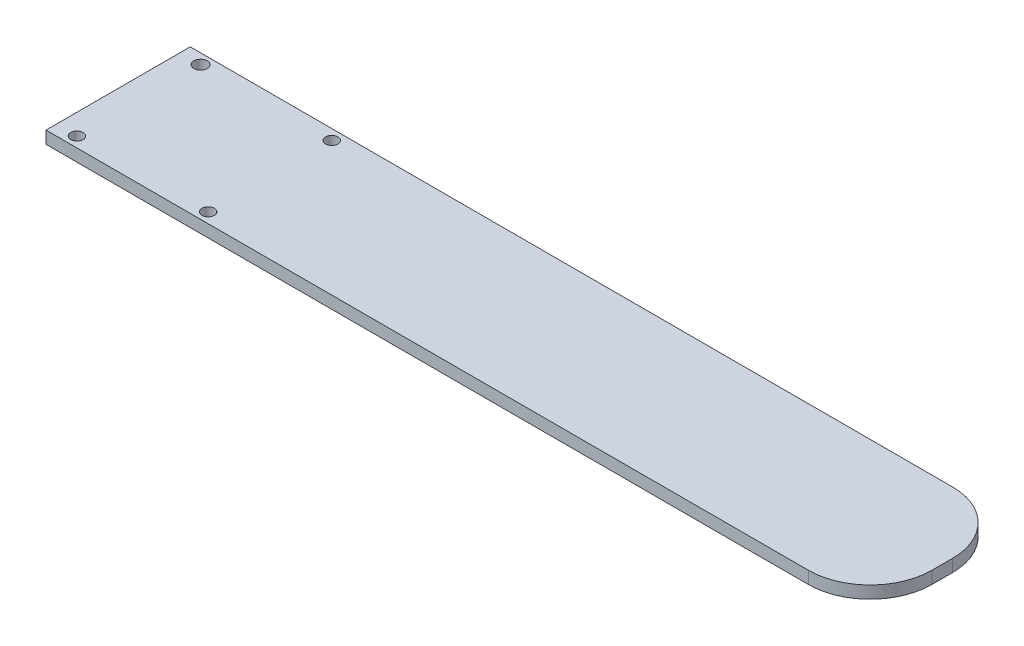
SolidWorks part; units mm, degrees
ref_plane "Front Plane" through (0, 0, 0) normal (0, 0, 1) x (1, 0, 0)
ref_plane "Top Plane" through (0, 0, 0) normal (0, 1, 0) x (1, 0, 0)
ref_plane "Right Plane" through (0, 0, 0) normal (1, 0, 0) x (0, 0, -1)
sketch "Sketch1" plane through (0, 0, 0) normal (0, 1, 0) x (1, 0, 0)
  line L1 (100, -17.5) -> (-100, -17.5)
  line L2 (100, -17.5) -> (100, 17.5)
  line L3 (100, 17.5) -> (-100, 17.5)
  line L4 (-100, -17.5) -> (-100, 17.5)
  line L5 (100, -17.5) -> (-100, 17.5) construction
  line L6 (100, 17.5) -> (-100, -17.5) construction
  point P0 (0, 0)
  dimension "D1" = 200
  dimension "D2" = 35
extrude "Boss-Extrude1" add sketch "Sketch1" along normal blind 3
fillet "Fillet1" radius 15 2 edges at (100, 1.5, -17.5) (100, 1.5, 17.5)
sketch "Sketch2" plane through (0, 3, 0) normal (0, 1, 0) x (1, 0, 0)
  line L1 (-100, 17.5) -> (-40, 17.5)
  line L2 (-100, 17.5) -> (-100, -17.5)
  line L3 (-100, -17.5) -> (-40, -17.5)
  line L4 (100, -2.5) -> (100, 2.5)
  line L5 (85, 17.5) -> (-100, 17.5)
  line L6 (-100, 17.5) -> (-100, -17.5)
  line L7 (-100, -17.5) -> (85, -17.5)
  line L8 (100, -2.5) -> (100, 2.5)
  line L9 (85, 17.5) -> (-100, 17.5)
  line L10 (-100, 17.5) -> (-100, -17.5)
  line L11 (-100, -17.5) -> (85, -17.5)
  line L12 (-40, 17.5) -> (-40, -17.5)
  line L13 (-63.144, -15) -> (-95, -15)
  line L14 (-63.144, -15) -> (-63.144, 15)
  line L15 (-63.144, 15) -> (-95, 15)
  line L16 (-95, -15) -> (-95, 15)
  line L17 (-63.144, -15) -> (-95, 15) construction
  line L18 (-63.144, 15) -> (-95, -15) construction
  circle A0 centre (-95, 15) radius 1.623
  circle A1 centre (-63.144, 15) radius 1.5
  arc A2 (100, 2.5) -> (85, 17.5) centre (85, 2.5) ccw
  arc A3 (85, -17.5) -> (100, -2.5) centre (85, -2.5) ccw
  arc A4 (100, 2.5) -> (85, 17.5) centre (85, 2.5) ccw
  arc A5 (85, -17.5) -> (100, -2.5) centre (85, -2.5) ccw
  circle A6 centre (-63.144, -15) radius 1.5
  circle A7 centre (-95, -15) radius 1.5
  point P9 (-79.072, 0)
  dimension "D7" = 3.246
  dimension "D8" = 3
  dimension "D9" = 3
  dimension "D10" = 3
  dimension "D2" = 60
  dimension "D3" = 31.856
  dimension "D4" = 30
  dimension "D5" = 2.5
  dimension "D6" = 5
  dimension "D1" = 0
extrude "Cut-Extrude1" cut sketch "Sketch2" against normal through all contours L15 A0 L16 | L16 A0 L15 | L16 A7 L13 | L13 A7 L16 | L13 A6 L14 | L14 A6 L13 | L14 A1 L15 | L15 A1 L14
equation "\"`15\"=25"
